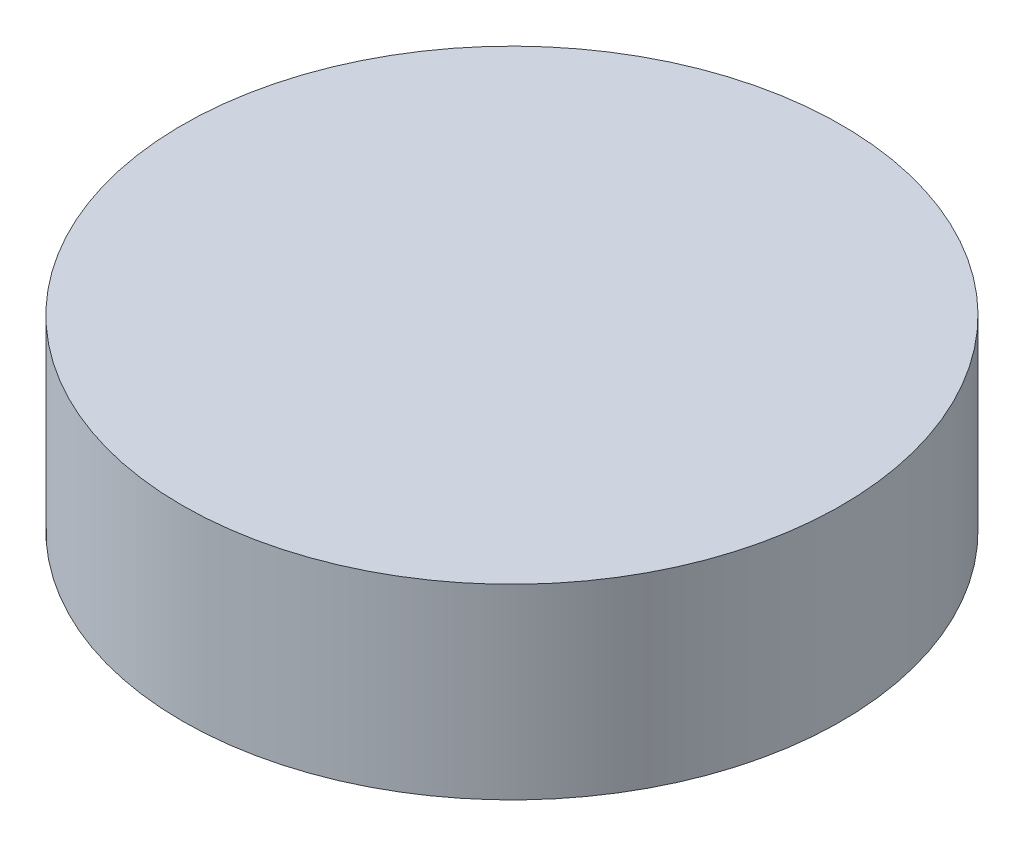
SolidWorks part; units mm, degrees
material "Plain Carbon Steel"
ref_plane "Front Plane" through (0, 0, 0) normal (0, 0, 1) x (1, 0, 0)
ref_plane "Top Plane" through (0, 0, 0) normal (0, 1, 0) x (1, 0, 0)
ref_plane "Right Plane" through (0, 0, 0) normal (1, 0, 0) x (0, 0, -1)
sketch "Sketch1" plane through (0, 0, 0) normal (0, 1, 0) x (1, 0, 0)
  circle A0 centre (0, 0) radius 15
  dimension "D1" = 30
extrude "Boss-Extrude1" add sketch "Sketch1" along normal blind 8.5
